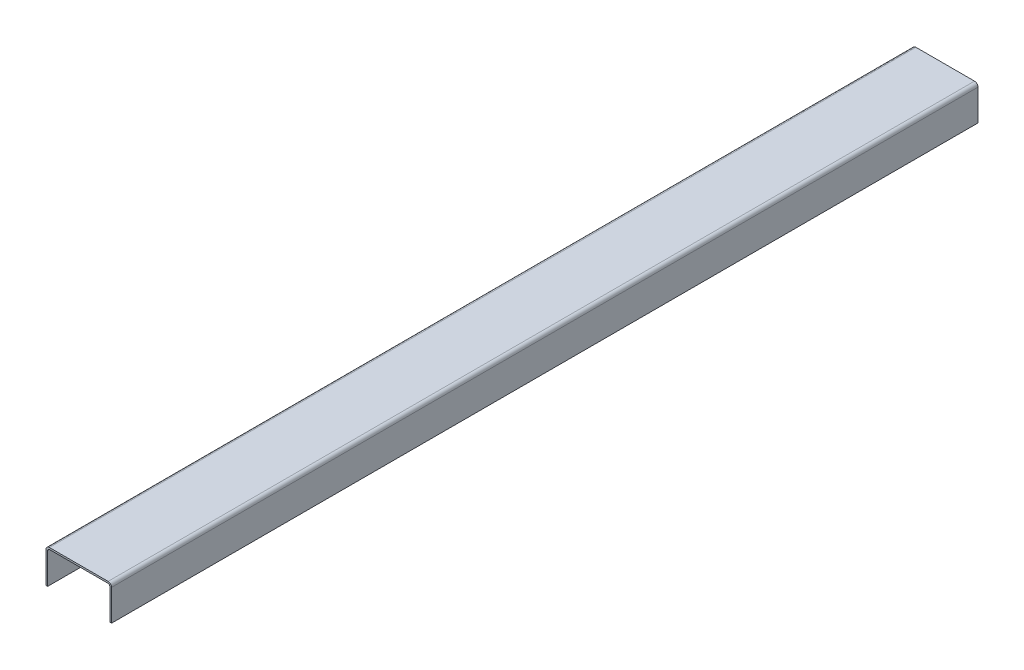
SolidWorks part; units mm, degrees
ref_plane "Front Plane" through (0, 0, 0) normal (0, 0, 1) x (1, 0, 0)
ref_plane "Top Plane" through (0, 0, 0) normal (0, 1, 0) x (1, 0, 0)
ref_plane "Right Plane" through (0, 0, 0) normal (1, 0, 0) x (0, 0, -1)
sketch "Sketch1" plane through (0, 0, 0) normal (0, 0, 1) x (1, 0, 0)
  line L0 (0, 0) -> (0, 18)
  line L1 (2, 20) -> (36, 20)
  line L2 (38, 18) -> (38, 0)
  line L3 (1, 0) -> (1, 18)
  line L4 (2, 19) -> (36, 19)
  line L5 (37, 18) -> (37, 0)
  line L6 (0, 0) -> (1, 0)
  line L7 (37, 0) -> (38, 0)
  arc A0 (0, 18) -> (2, 20) centre (2, 18) cw
  arc A1 (36, 20) -> (38, 18) centre (36, 18) cw
  arc A2 (1, 18) -> (2, 19) centre (2, 18) cw
  arc A3 (36, 19) -> (37, 18) centre (36, 18) cw
  point P8 (0, 20)
  point P11 (38, 20)
  dimension "D3" = 2
  dimension "D1" = 38
  dimension "D2" = 20
  dimension "D4" = 1
extrude "Boss-Extrude1" add sketch "Sketch1" along normal blind 502.33
